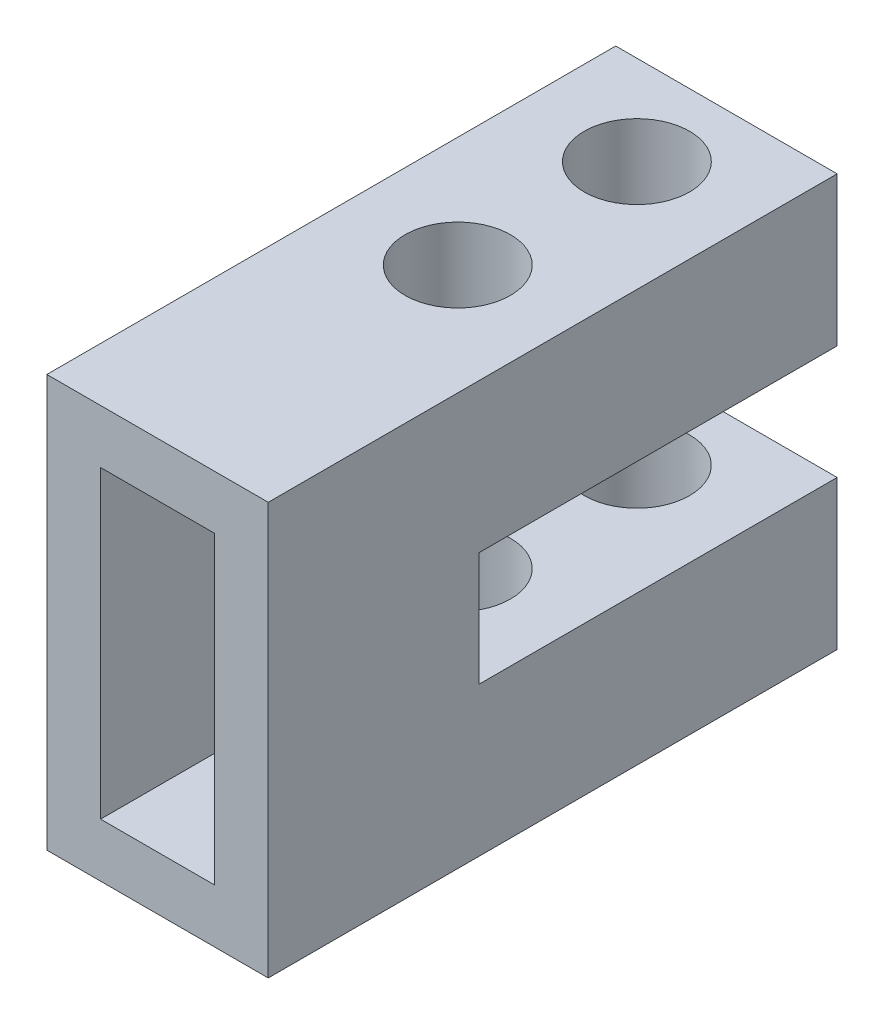
SolidWorks part; units mm, degrees
ref_plane "Front Plane" through (0, 0, 0) normal (0, 0, 1) x (1, 0, 0)
ref_plane "Top Plane" through (0, 0, 0) normal (0, 1, 0) x (1, 0, 0)
ref_plane "Right Plane" through (0, 0, 0) normal (1, 0, 0) x (0, 0, -1)
sketch "Sketch1" plane through (0, 0, 0) normal (0, 0, 1) x (1, 0, 0)
  line L1 (0, 0) -> (3.18, 0)
  line L2 (0, 0) -> (0, 8.5)
  line L3 (0, 8.5) -> (3.18, 8.5)
  line L4 (3.18, 0) -> (3.18, 8.5)
  line L5 (-1.5, 10) -> (4.68, 10)
  line L6 (-1.5, 10) -> (-1.5, -1.5)
  line L7 (-1.5, -1.5) -> (4.68, -1.5)
  line L8 (4.68, 10) -> (4.68, -1.5)
  dimension "D1" = 8.5
  dimension "D2" = 3.18
  dimension "D3" = 1.5
  dimension "D4" = 1.5
  dimension "D5" = 1.5
  dimension "D6" = 1.5
extrude "Boss-Extrude1" add sketch "Sketch1" along normal blind 4.88
sketch "Sketch2" plane through (0, 0, 0) normal (0, 0, -1) x (-1, 0, 0)
  line L1 (-4.68, 10) -> (1.5, 10)
  line L2 (-4.68, 10) -> (-4.68, -1.5)
  line L3 (-4.68, -1.5) -> (1.5, -1.5)
  line L4 (1.5, 10) -> (1.5, -1.5)
extrude "Boss-Extrude2" add sketch "Sketch2" along normal blind 1
sketch "Sketch3" plane through (0, 0, -1) normal (0, 0, -1) x (-1, 0, 0)
  line L0 (1.5, -1.5) -> (1.5, 10) construction
  line L1 (-4.68, 10) -> (1.5, 10)
  line L2 (-4.68, 10) -> (-4.68, 5.84)
  line L3 (-4.68, 5.84) -> (1.5, 5.84)
  line L4 (1.5, 10) -> (1.5, 5.84)
  line L6 (-4.68, -1.5) -> (1.5, -1.5)
  line L7 (-4.68, -1.5) -> (-4.68, 2.66)
  line L8 (-4.68, 2.66) -> (1.5, 2.66)
  line L9 (1.5, -1.5) -> (1.5, 2.66)
  dimension "D1" = 3.18
extrude "Boss-Extrude3" add sketch "Sketch3" along normal blind 10
sketch "Sketch4" plane through (0, 10, 0) normal (0, 1, 0) x (1, 0, 0)
  line L0 (1.59, 11) -> (1.59, -4.88) construction
  line L1 (-1.5, 11) -> (4.68, 11) construction
  line L2 (4.68, -4.88) -> (-1.5, -4.88) construction
  line L4 (26.59, 1) -> (-23.41, 1) construction
  circle A0 centre (1.59, 3.5) radius 1.47
  circle A1 centre (1.59, 8.5) radius 1.47
  dimension "D1" = 2.94
  dimension "D2" = 2.94
  dimension "D3" = 2.5
  dimension "D4" = 2.5
extrude "Cut-Extrude1" cut sketch "Sketch4" against normal through all
